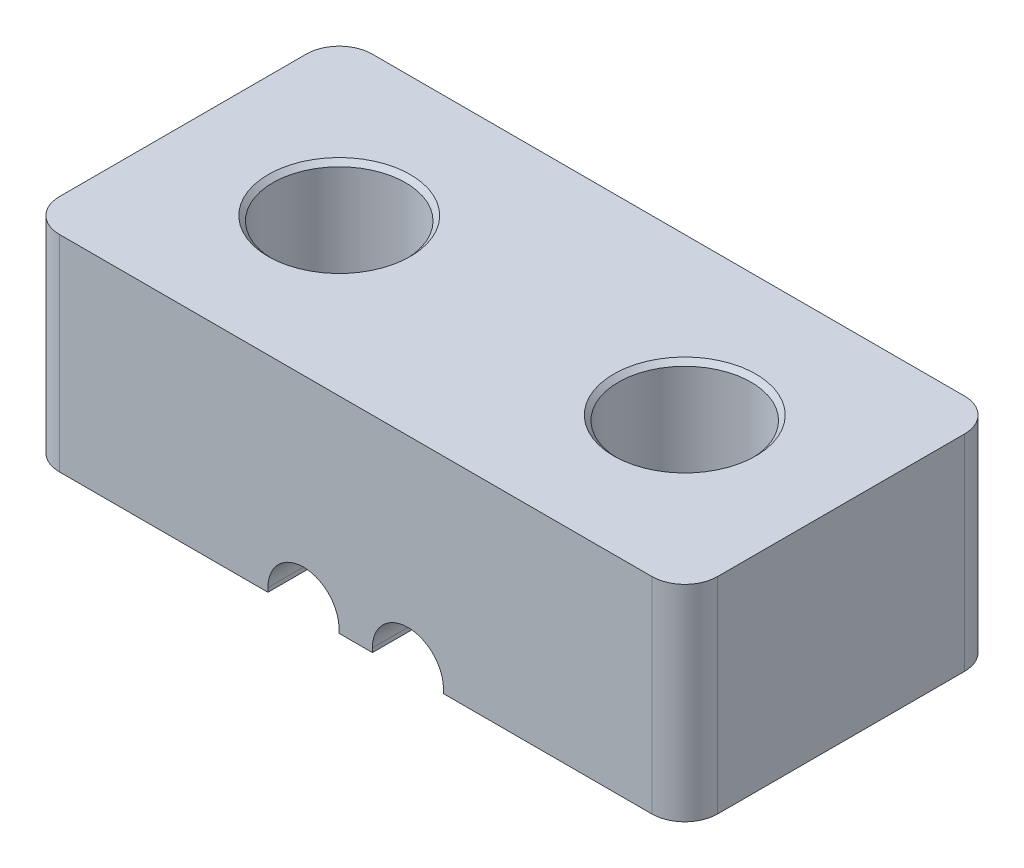
SolidWorks part; units mm, degrees
ref_plane "PL-01 Front" through (0, 0, 0) normal (0, 0, 1) x (1, 0, 0)
ref_plane "PL-02 Top" through (0, 0, 0) normal (0, 1, 0) x (1, 0, 0)
ref_plane "PL-03 Right" through (0, 0, 0) normal (1, 0, 0) x (0, 0, -1)
sketch "Sketch1" plane through (0, 0, 0) normal (0, 1, 0) x (1, 0, 0)
  line L1 (-4, 1.9) -> (4, 1.9)
  line L2 (-4, 1.9) -> (-4, -1.9)
  line L3 (-4, -1.9) -> (4, -1.9)
  line L4 (4, 1.9) -> (4, -1.9)
  point P4 (0, 1.9)
  point P5 (4, 0)
  dimension "D1" = 3.8
  dimension "D2" = 8
extrude "BE-01 Boss Extrude" add sketch "Sketch1" along normal blind 2.5
sketch "Sketch2" plane through (0, 0, 0) normal (0, 0, 1) x (1, 0, 0)
  line L0 (0, 2.3828) -> (0, 3.7717) construction
  line L1 (-6.9787, -2.49) -> (-6.9787, -4.2113)
  line L2 (-1.0668, -2.49) -> (-6.9787, -2.49)
  line L3 (-0.2032, -2.49) -> (0.2032, -2.49)
  line L4 (0.2032, -2.49) -> (0.2032, 0.05)
  line L5 (1.0668, 0.05) -> (1.0668, -2.49)
  line L6 (1.0668, -2.49) -> (6.9787, -2.49)
  line L7 (6.9787, -2.49) -> (6.9787, -4.2113)
  line L8 (6.9787, -4.2113) -> (-6.9787, -4.2113)
  line L9 (-1.0668, 0.05) -> (-1.0668, -2.49)
  line L10 (-0.2032, -2.49) -> (-0.2032, 0.05)
  arc A0 (-0.2032, 0.05) -> (-1.0668, 0.05) centre (-0.635, 0.05) ccw
  arc A1 (0.2032, 0.05) -> (1.0668, 0.05) centre (0.635, 0.05) cw
  dimension "D2" = 0.4318
  dimension "D1" = 0.635
  dimension "D3" = 2.54
  dimension "D4" = 0.05
extrude "CE-01 Clamp Grooves" cut sketch "Sketch2" against normal mid plane 6
hole_wizard "#52 (0.0635) Diameter Hole1" positions "Sketch5" profile "Sketch4" hole size "#52" standard "Ansi Inch" end condition up to next
sketch "Sketch5" plane through (0, 2.5, 0) normal (0, 1, 0) x (-1, 0, 0)
  point P0 (2.1, 0)
  point P1 (-2.1, 0)
  dimension "D1" = 2.1
  dimension "D2" = 2.1
sketch "Sketch4" plane through (-2.1, 2.5, 0) normal (1, 0, 0) x (0, 0, 1)
  line L0 (0, 0) -> (0, 2.5)
  line L1 (0, 2.5) -> (0.8636, 2.5)
  line L2 (0.8064, 2.4428) -> (0.8064, 0.0571)
  line L3 (0.8064, 0.0571) -> (0.8636, 0)
  line L5 (0.8636, 0) -> (0, 0)
  line L6 (-0.8064, 0.0571) -> (-0.8636, 0) construction
  line L7 (0.8636, 2.5) -> (0.8064, 2.4428)
  line L8 (-0.8636, 2.5) -> (-0.8065, 2.4428) construction
  line L11 (0, -6.35) -> (0, 107.95) construction
  dimension "Thru Hole Dia." = 1.6129
  dimension "Thru Hole Depth" = 2.5
  dimension "Near C'Sink Dia." = 1.7272
  dimension "Near C'Sink Angle" = 90
  dimension "Far C'Sink Dia." = 1.7272
  dimension "Far C'Sink Angle" = 90
fillet "Fillet1" radius 0.4 4 edges at (-4, 1.25, -1.9) (4, 1.25, -1.9) (-4, 1.25, 1.9) (4, 1.25, 1.9)
